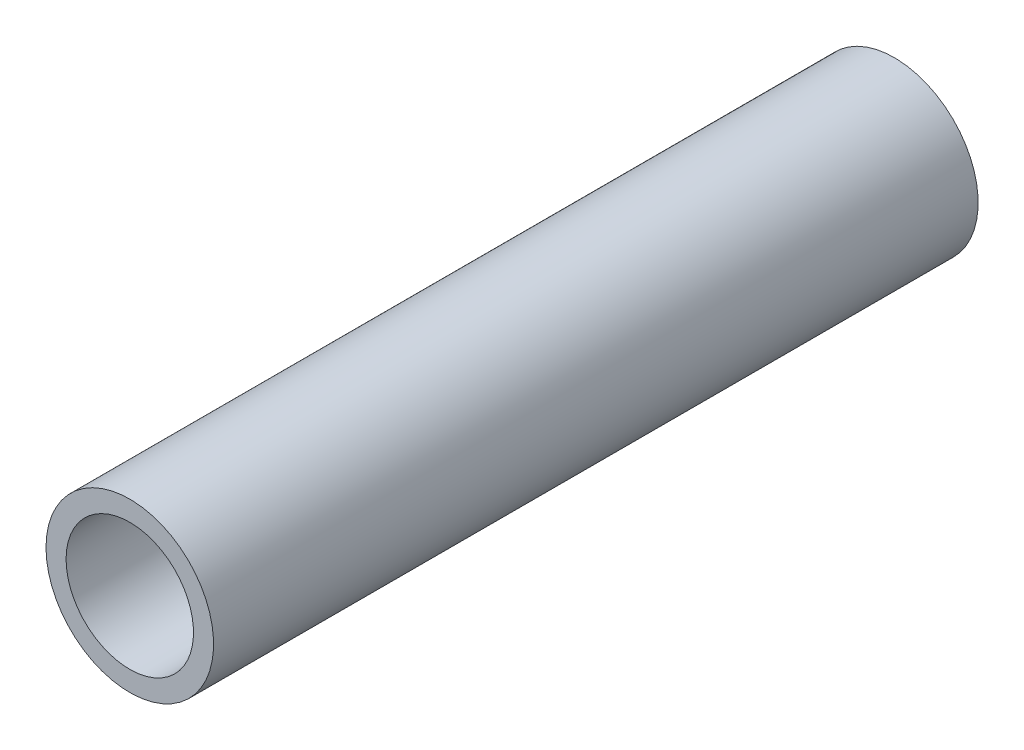
SolidWorks part; units mm, degrees
material "Plain Carbon Steel"
ref_plane "Front Plane" through (0, 0, 0) normal (0, 0, 1) x (1, 0, 0)
ref_plane "Top Plane" through (0, 0, 0) normal (0, 1, 0) x (1, 0, 0)
ref_plane "Right Plane" through (0, 0, 0) normal (1, 0, 0) x (0, 0, -1)
sketch "Sketch1" plane through (0, 0, 0) normal (0, 0, 1) x (1, 0, 0)
  circle A0 centre (0, 0) radius 12.7
  circle A1 centre (0, 0) radius 16.7005
extrude "Boss-Extrude1" add sketch "Sketch1" along normal blind 152.4
